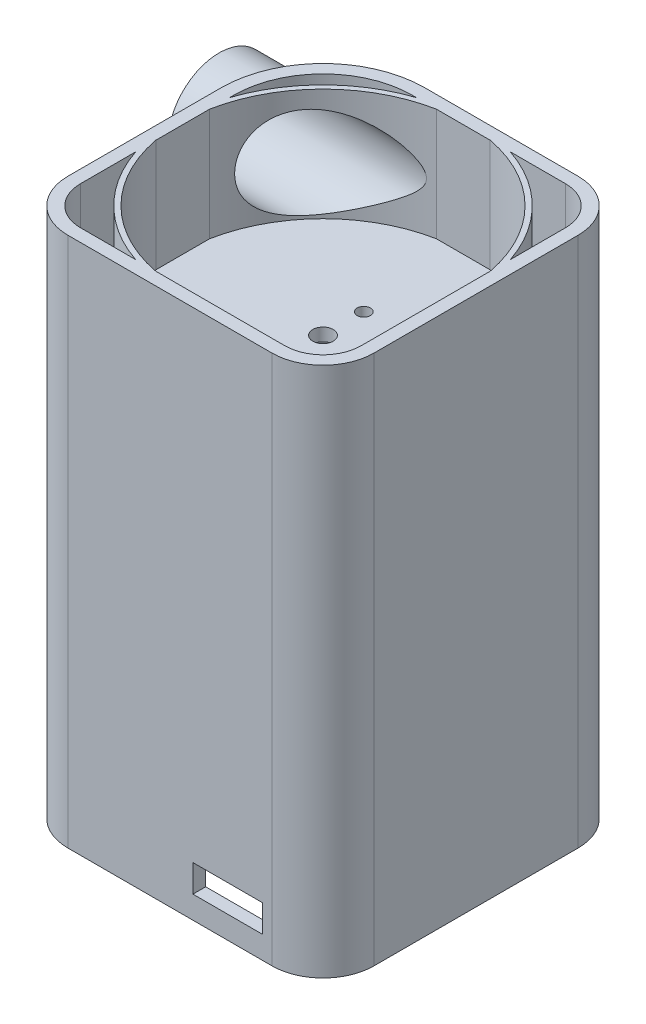
SolidWorks part; units mm, degrees
ref_plane "Front Plane" through (0, 0, 0) normal (0, 0, 1) x (1, 0, 0)
ref_plane "Top Plane" through (0, 0, 0) normal (0, 1, 0) x (1, 0, 0)
ref_plane "Right Plane" through (0, 0, 0) normal (1, 0, 0) x (0, 0, -1)
sketch "Sketch2" plane through (0, 0, 0) normal (0, 1, 0) x (1, 0, 0)
  line L1 (-10, 30) -> (20, 30)
  line L2 (-30, 10) -> (-30, -20)
  line L3 (-20, -30) -> (20, -30)
  line L4 (30, 20) -> (30, -20)
  line L5 (-30, 30) -> (30, -30) construction
  line L6 (-30, -30) -> (30, 30) construction
  arc A0 (-10, 30) -> (-30, 10) centre (-10, 10) ccw
  arc A1 (-30, -20) -> (-20, -30) centre (-20, -20) ccw
  arc A2 (20, -30) -> (30, -20) centre (20, -20) ccw
  arc A3 (20, 30) -> (30, 20) centre (20, 20) cw
  point P0 (0, 0)
  dimension "D3" = 20
  dimension "D4" = 10
  dimension "D1" = 60
  dimension "D2" = 60
extrude "Boss-Extrude1" add sketch "Sketch2" along normal blind 82
shell "Shell1" thickness 2.5
sketch "Sketch5" plane through (0, 82, 0) normal (0, 1, 0) x (1, 0, 0)
  line L4 (-30, 10) -> (-30, -20)
  line L5 (-20, -30) -> (20, -30)
  line L6 (30, -20) -> (30, 20)
  line L7 (20, 30) -> (-10, 30)
  line L8 (-30, 10) -> (-30, -20)
  line L9 (-20, -30) -> (20, -30)
  line L10 (30, -20) -> (30, 20)
  line L11 (20, 30) -> (-10, 30)
  arc A4 (-10, 30) -> (-30, 10) centre (-10, 10) ccw
  arc A5 (-30, -20) -> (-20, -30) centre (-20, -20) ccw
  arc A6 (20, -30) -> (30, -20) centre (20, -20) ccw
  arc A7 (30, 20) -> (20, 30) centre (20, 20) ccw
  arc A8 (-10, 30) -> (-30, 10) centre (-10, 10) ccw
  arc A9 (-30, -20) -> (-20, -30) centre (-20, -20) ccw
  arc A10 (20, -30) -> (30, -20) centre (20, -20) ccw
  arc A11 (30, 20) -> (20, 30) centre (20, 20) ccw
  dimension "D1" = 0
extrude "Boss-Extrude2" add sketch "Sketch5" along normal blind 22
shell "Shell2" thickness 2.5
ref_plane "Plane1" through (0, 114, 0) normal (0, 1, 0) x (1, 0, 0)
sketch "Sketch6" plane through (0, 82, 0) normal (0, 1, 0) x (1, 0, 0)
  line L0 (0, 0) -> (-0.7232, -28.991) construction
  line L1 (0, 0) -> (29, 0) construction
  line L2 (-0.7232, -28.991) -> (-0.6983, -27.9913)
  line L3 (28, 0) -> (29, 0)
  arc A0 (29, 0) -> (-0.7232, -28.991) centre (0, 0) ccw
  arc A1 (28, 0) -> (-0.6983, -27.9913) centre (0, 0) ccw
  dimension "D1" = 58
  dimension "D2" = 1
extrude "Boss-Extrude7" add sketch "Sketch6" along normal up to surface (22 mm away) up to face at (0.9911, 104, 0.9911)
sketch "Sketch7" plane through (0, 82, 0) normal (0, 1, 0) x (1, 0, 0)
  circle A0 centre (0, 0) radius 2
  circle A1 centre (0, 8) radius 1.3
  circle A2 centre (0, -8) radius 1.3
  dimension "D1" = 4
  dimension "D2" = 2.6
  dimension "D3" = 16
  dimension "D4" = 8
extrude "Cut-Extrude1" cut sketch "Sketch7" against normal blind 10
sketch "Sketch8" plane through (0, 79.5, 0) normal (0, -1, 0) x (1, 0, 0)
  circle A0 centre (0, 0) radius 15.2
  circle A1 centre (0, 0) radius 16
  dimension "D1" = 0.8
  dimension "D2" = 32
extrude "Boss-Extrude8" add sketch "Sketch8" along normal blind 6
ref_plane "Plane2" through (-38.5, 0, 0) normal (-1, 0, 0) x (0, 0, 1)
sketch "Sketch10" plane through (-38.5, 0, 0) normal (-1, 0, 0) x (0, 0, 1)
  circle A0 centre (-18.1447, 91.6227) radius 10
  circle A1 centre (-18.1447, 91.6227) radius 9
  dimension "D1" = 20
  dimension "D2" = 1
extrude "Boss-Extrude9" add sketch "Sketch10" against normal blind 30
sketch "Sketch13" plane through (-38.5, 0, 0) normal (-1, 0, 0) x (0, 0, 1)
  circle A0 centre (-18.1447, 91.6227) radius 9 construction
  circle A1 centre (-18.1447, 91.6227) radius 9
extrude "Cut-Extrude2" cut sketch "Sketch13" against normal blind 40
sketch "Sketch14" plane through (0, 104, 0) normal (0, 1, 0) x (1, 0, 0)
  line L0 (-27.5, 5.2678) -> (-27.5, -5.2678) construction
  line L1 (-5.2678, -27.5) -> (20, -27.5) construction
  line L2 (27.5, -20) -> (27.5, 5.2678) construction
  line L3 (5.2678, 27.5) -> (-5.2678, 27.5) construction
  line L4 (-27.5, 5.2678) -> (-27.5, -5.2678)
  line L5 (-5.2678, -27.5) -> (20, -27.5)
  line L6 (27.5, -20) -> (27.5, 5.2678)
  line L7 (5.2678, 27.5) -> (-5.2678, 27.5)
  arc A0 (-27.5, -5.2678) -> (-5.2678, -27.5) centre (0, 0) ccw construction
  arc A1 (20, -27.5) -> (27.5, -20) centre (20, -20) ccw construction
  arc A2 (27.5, 5.2678) -> (5.2678, 27.5) centre (0, 0) ccw construction
  arc A3 (-5.2678, 27.5) -> (-27.5, 5.2678) centre (0, 0) ccw construction
  arc A4 (-27.5, -5.2678) -> (-5.2678, -27.5) centre (0, 0) ccw
  arc A5 (20, -27.5) -> (27.5, -20) centre (20, -20) ccw
  arc A6 (27.5, 5.2678) -> (5.2678, 27.5) centre (0, 0) ccw
  arc A7 (-5.2678, 27.5) -> (-27.5, 5.2678) centre (0, 0) ccw
extrude "Cut-Extrude3" cut sketch "Sketch14" against normal up to surface (22 mm away) up to face at (-3.6423, 82, -4.7841)
sketch "Sketch15" plane through (0, 79.5, 0) normal (0, -1, 0) x (1, 0, 0)
  arc A0 (3.7036, -21.3934) -> (-2.0086, -21.3934) centre (0.8475, -22.3113) ccw
  arc A1 (-2.0086, -23.2292) -> (3.7036, -23.2292) centre (0.8475, -22.3113) ccw
  ellipse E0 centre (0.8475, -22.3113) end of major axis (-6.1525, -22.3113) minor radius 1.0054 (3.7036, -23.2292) -> (3.7036, -21.3934) ccw
  ellipse E1 centre (0.8475, -22.3113) end of major axis (-6.1525, -22.3113) minor radius 1.0054 (-2.0086, -21.3934) -> (-2.0086, -23.2292) ccw
  dimension "D2" = 14
extrude "Boss-Extrude10" add sketch "Sketch15" along normal blind 40
sketch "Sketch16" plane through (0, 0, 30) normal (0, 0, 1) x (1, 0, 0)
  line L1 (4.5139, 9.791) -> (18.1725, 9.791)
  line L2 (4.5139, 9.791) -> (4.5139, 4.4276)
  line L3 (4.5139, 4.4276) -> (18.1725, 4.4276)
  line L4 (18.1725, 9.791) -> (18.1725, 4.4276)
  line L5 (4.5139, 9.791) -> (18.1725, 4.4276) construction
  line L6 (4.5139, 4.4276) -> (18.1725, 9.791) construction
  point P4 (11.3432, 7.1093)
extrude "Cut-Extrude4" cut sketch "Sketch16" against normal blind 10
